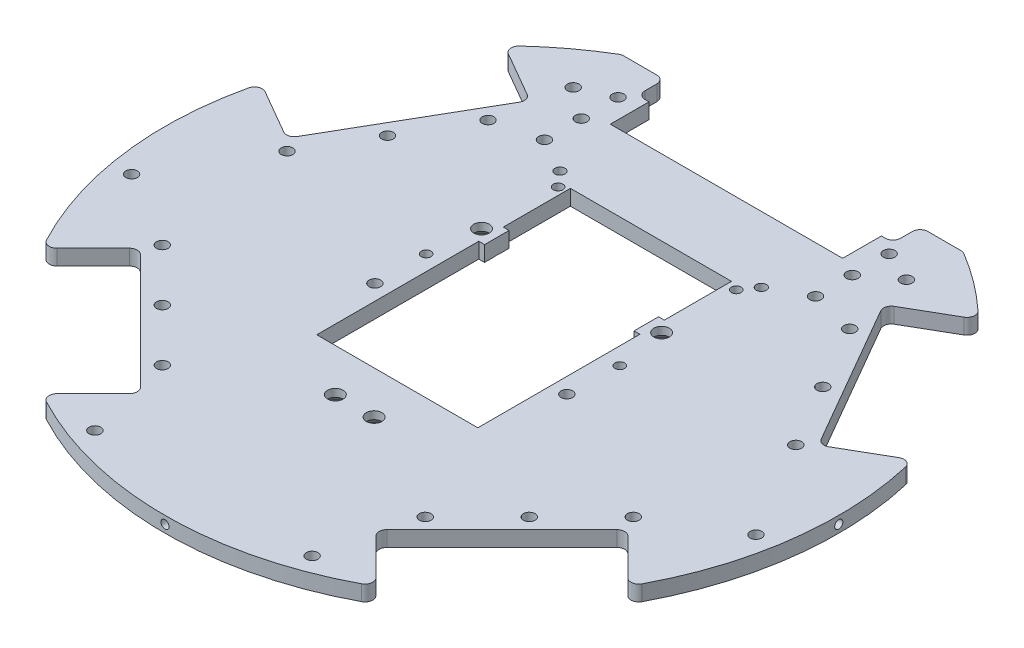
SolidWorks part; units mm, degrees
ref_plane "Front Plane" through (0, 0, 0) normal (0, 0, 1) x (1, 0, 0)
ref_plane "Top Plane" through (0, 0, 0) normal (0, 1, 0) x (1, 0, 0)
ref_plane "Right Plane" through (0, 0, 0) normal (1, 0, 0) x (0, 0, -1)
sketch "Sketch1" plane through (0, 0, 0) normal (0, 1, 0) x (1, 0, 0)
  line L0 (0, 75) -> (0, -70.0325) construction
  line L1 (0, 0) -> (57.1577, 33) construction
  line L2 (0, 0) -> (46.669, -46.669) construction
  line L3 (45.6577, 52.9186) -> (68.6577, 13.0814)
  line L4 (-44.0908, 75) -> (44.0908, 75) construction
  line L5 (62.9325, -30.4056) -> (30.4056, -62.9325)
  line L6 (45.6577, 52.9186) -> (61.1636, 61.8709)
  line L7 (68.6577, 13.0814) -> (84.1636, 22.0338)
  line L8 (30.4056, -62.9325) -> (43.0661, -75.593)
  line L9 (62.9325, -30.4056) -> (75.593, -43.0661)
  line L10 (-33, 69) -> (33, 69)
  line L11 (33, 69) -> (33, 75)
  line L12 (33, 75) -> (44.0908, 75)
  line L13 (0, 0) -> (-46.669, -46.669) construction
  line L14 (0, 0) -> (-57.1577, 33) construction
  line L15 (-33, 75) -> (-44.0908, 75)
  line L16 (-33, 69) -> (-33, 75)
  line L17 (-62.9325, -30.4056) -> (-75.593, -43.0661)
  line L18 (-30.4056, -62.9325) -> (-43.0661, -75.593)
  line L19 (-68.6577, 13.0814) -> (-84.1636, 22.0338)
  line L20 (-45.6577, 52.9186) -> (-61.1636, 61.8709)
  line L21 (-62.9325, -30.4056) -> (-30.4056, -62.9325)
  line L22 (-45.6577, 52.9186) -> (-68.6577, 13.0814)
  arc A0 (-43.0661, -75.593) -> (43.0661, -75.593) centre (0, 0) ccw
  arc A1 (61.1636, 61.8709) -> (44.0908, 75) centre (0, 0) ccw
  arc A2 (75.593, -43.0661) -> (84.1636, 22.0338) centre (0, 0) ccw
  arc A3 (-75.593, -43.0661) -> (-84.1636, 22.0338) centre (0, 0) cw
  arc A4 (-61.1636, 61.8709) -> (-44.0908, 75) centre (0, 0) cw
  point P27 (0, 69)
  dimension "D1" = 87
  dimension "D2" = 75
  dimension "D3" = 66
  dimension "D4" = 60
  dimension "D5" = 45
  dimension "D6" = 46
  dimension "D7" = 46
  dimension "D8" = 33
  dimension "D9" = 6
extrude "Boss-Extrude1" add sketch "Sketch1" along normal mid plane 4
fillet "Fillet1" radius 2 20 edges at (33, 0, -75) (-33, 0, -75) (44.0908, 0, -75) (68.6577, 0, -13.0814) (84.1636, 0, -22.0338) (45.6577, 0, -52.9186) (61.1636, 0, -61.8709) (62.9325, 0, 30.4056) (43.0661, 0, 75.593) (30.4056, 0, 62.9325) (75.593, 0, 43.0661) (-43.0661, 0, 75.593) (-30.4056, 0, 62.9325) (-75.593, 0, 43.0661) (-62.9325, 0, 30.4056) (-68.6577, 0, -13.0814) (-84.1636, 0, -22.0338) (-45.6577, 0, -52.9186) (-44.0908, 0, -75) (-61.1636, 0, -61.8709)
sketch "Sketch2" plane through (0, -2, 0) normal (0, -1, 0) x (-1, 0, 0)
  line L0 (46.6936, 43.1244) -> (65.6936, 10.2154) construction
  line L1 (60.8112, -26.8701) -> (33.9411, -53.7401) construction
  line L2 (46.6577, 51.1865) -> (67.6577, 14.8135) construction
  line L3 (61.5183, -31.8198) -> (31.8198, -61.5183) construction
  line L4 (70.3897, 14.0814) -> (81.8562, 20.7016) construction
  line L5 (73.7091, -41.1822) -> (64.3467, -31.8198) construction
  line L6 (35, 65) -> (35, 46) construction
  line L7 (26, 61) -> (26, 41) construction
  line L8 (35, 75) -> (43.5431, 75) construction
  line L9 (-33, 69) -> (33, 69) construction
  line L10 (-33, 69) -> (33, 69) construction
  line L11 (0, 69) -> (0, -87) construction
  line L12 (-26, 61) -> (-26, 41) construction
  line L13 (-35, 65) -> (-35, 46) construction
  line L14 (-60.8112, -26.8701) -> (-33.9411, -53.7401) construction
  line L15 (-46.6936, 43.1244) -> (-65.6936, 10.2154) construction
  arc A0 (-40.7037, -76.8909) -> (40.7037, -76.8909) centre (0, 0) ccw construction
  point P0 (46.6936, 43.1244)
  point P1 (56.1936, 26.6699)
  point P2 (65.6936, 10.2154)
  point P3 (60.8112, -26.8701)
  point P4 (47.3762, -40.3051)
  point P5 (33.9411, -53.7401)
  point P18 (35, 65)
  point P19 (35, 55.5)
  point P20 (35, 46)
  point P21 (26, 61)
  point P22 (26, 41)
  point P29 (0, 69)
  point P34 (0, 69)
  point P48 (-35, 55.5)
  point P49 (-47.3762, -40.3051)
  point P50 (-56.1936, 26.6699)
  dimension "D1" = 38
  dimension "D2" = 38
  dimension "D3" = 4
  dimension "D4" = 4
  dimension "D5" = 18
  dimension "D6" = 18
  dimension "D7" = 19
  dimension "D8" = 35
  dimension "10" = 10
  dimension "D9" = 20
  dimension "D10" = 8
  dimension "D11" = 26
hole_wizard "CSK for M3 SFHCS1" positions "3DSketch1" profile "Sketch3" countersink size "M3" standard "ANSI Metric"
sketch3d "3DSketch1"
  point P0 (46.6936, -2, -43.1244)
  point P3 (56.1936, -2, -26.6699)
  point P6 (65.6936, -2, -10.2154)
  point P9 (60.8112, -2, 26.8701)
  point P12 (47.3762, -2, 40.3051)
  point P15 (33.9411, -2, 53.7401)
  point P18 (-33.9411, -2, 53.7401)
  point P21 (-47.3762, -2, 40.3051)
  point P24 (-60.8112, -2, 26.8701)
  point P27 (-46.6936, -2, -43.1244)
  point P30 (-56.1936, -2, -26.6699)
  point P33 (-65.6936, -2, -10.2154)
  point P36 (-35, -2, -65)
  point P39 (-35, -2, -55.5)
  point P42 (-35, -2, -46)
  point P45 (35, -2, -46)
  point P48 (35, -2, -55.5)
  point P51 (35, -2, -65)
sketch "Sketch3" plane through (46.6936, -2, -43.1244) normal (1, 0, 0) x (0, 0, -1)
  line L0 (0, 0) -> (0, 10.4013)
  line L1 (0, 10.4013) -> (1.5, 9.5)
  line L2 (1.5, 9.5) -> (1.5, 1.3)
  line L3 (1.5, 1.3) -> (2.8, 0)
  line L5 (2.8, 0) -> (0, 0)
  line L6 (-1.5, 1.3) -> (-2.8, 0) construction
  line L10 (0, 10.4013) -> (-1.5, 9.5) construction
  line L11 (0, -6.35) -> (0, 107.95) construction
  dimension "Hole Dia." = 3
  dimension "Hole Depth" = 9.5
  dimension "Near C'Sink Dia." = 5.6
  dimension "Near C'Sink Angle" = 90
  dimension "Drill Angle" = 118
sketch "Sketch4" plane through (0, -2, 0) normal (0, -1, 0) x (1, 0, 0)
  line L0 (0, 0) -> (-43.0182, -61.4364) construction
  line L1 (0, 0) -> (-28.0457, 77.0548) construction
  line L2 (0, -69) -> (0, 87) construction
  line L3 (0, 0) -> (-80.6164, 15) construction
  line L4 (0, -69) -> (0, 87) construction
  line L5 (0, 0) -> (80.6164, 15) construction
  line L6 (0, 0) -> (28.0457, 77.0548) construction
  line L7 (0, 0) -> (43.0182, -61.4364) construction
  dimension "D1" = 75
  dimension "D2" = 35
  dimension "D3" = 82
  dimension "D4" = 20
  dimension "D5" = 82
  dimension "D6" = 15
hole_wizard "CSK for M3 SFHCS2" positions "3DSketch2" profile "Sketch5" countersink size "M3" standard "ANSI Metric"
sketch3d "3DSketch2"
  point P0 (43.0182, -2, -61.4364)
  point P3 (80.6164, -2, 15)
  point P6 (28.0457, -2, 77.0548)
  point P9 (-28.0457, -2, 77.0548)
  point P12 (-80.6164, -2, 15)
  point P15 (-43.0182, -2, -61.4364)
sketch "Sketch5" plane through (43.0182, -2, -61.4364) normal (1, 0, 0) x (0, 0, -1)
  line L0 (0, 0) -> (0, 10.4013)
  line L1 (0, 10.4013) -> (1.5, 9.5)
  line L2 (1.5, 9.5) -> (1.5, 1.3)
  line L3 (1.5, 1.3) -> (2.8, 0)
  line L5 (2.8, 0) -> (0, 0)
  line L6 (-1.5, 1.3) -> (-2.8, 0) construction
  line L10 (0, 10.4013) -> (-1.5, 9.5) construction
  line L11 (0, -6.35) -> (0, 107.95) construction
  dimension "Hole Dia." = 3
  dimension "Hole Depth" = 9.5
  dimension "Near C'Sink Dia." = 5.6
  dimension "Near C'Sink Angle" = 90
  dimension "Drill Angle" = 118
hole_wizard "CSK for M3 SFHCS3" positions "3DSketch3" profile "Sketch6" countersink size "M3" standard "ANSI Metric"
sketch3d "3DSketch3"
  point P0 (26, -2, -41)
  point P3 (26, -2, -61)
  point P6 (-26, -2, -41)
  point P9 (-26, -2, -61)
sketch "Sketch6" plane through (26, -2, -41) normal (1, 0, 0) x (0, 0, -1)
  line L0 (0, 0) -> (0, 10.2811)
  line L1 (0, 10.2811) -> (1.3, 9.5)
  line L2 (1.3, 9.5) -> (1.3, 1)
  line L3 (1.3, 1) -> (2.3, 0)
  line L5 (2.3, 0) -> (0, 0)
  line L6 (-1.3, 1) -> (-2.3, 0) construction
  line L10 (0, 10.2811) -> (-1.3, 9.5) construction
  line L11 (0, -6.35) -> (0, 107.95) construction
  dimension "Hole Dia." = 2.6
  dimension "Hole Depth" = 9.5
  dimension "Near C'Sink Dia." = 4.6
  dimension "Near C'Sink Angle" = 90
  dimension "Drill Angle" = 118
sketch "Sketch7" plane through (0, 0, 0) normal (0, 1, 0) x (1, 0, 0)
  arc A0 (-84.8058, 19.4159) -> (-76.8909, -40.7037) centre (0, 0) ccw construction
  arc A1 (76.8909, -40.7037) -> (84.8058, 19.4159) centre (0, 0) ccw construction
  arc A2 (-40.7037, -76.8909) -> (40.7037, -76.8909) centre (0, 0) ccw construction
  arc A3 (59.2176, 63.736) -> (44.5676, 74.7176) centre (0, 0) ccw construction
  arc A4 (-44.5676, 74.7176) -> (-59.2176, 63.736) centre (0, 0) ccw construction
  point P0 (-86.2557, -11.3558)
  point P1 (86.2557, -11.3558)
  point P5 (0, -87)
  point P9 (52.1823, 69.6133)
  point P13 (-52.1823, 69.6133)
ref_plane "Plane1" through (87, 0, 0) normal (1, 0, 0) x (0, 0, -1)
sketch "Sketch9" plane through (87, 0, 0) normal (1, 0, 0) x (0, 0, -1)
  circle A0 centre (0, 0) radius 1.05
  dimension "D1" = 2.1
ref_plane "Plane2" through (0, 0, 87) normal (0, 0, 1) x (1, 0, 0)
sketch "Sketch10" plane through (0, 0, 87) normal (0, 0, 1) x (1, 0, 0)
  circle A0 centre (0, 0) radius 1.05
  dimension "D1" = 2.1
ref_plane "Plane3" through (52.1823, 0, -69.6133) normal (0.5998, 0, -0.8002) x (-0.8002, 0, -0.5998)
sketch "Sketch11" plane through (52.1823, 0, -69.6133) normal (0.5998, 0, -0.8002) x (-0.8002, 0, -0.5998)
  circle A0 centre (0, 0) radius 1.05
  dimension "D1" = 2.1
sketch "Sketch12" plane through (0, 2, 0) normal (0, 1, 0) x (1, 0, 0)
  line L0 (-23.25, 18) -> (23.25, 18) construction
  line L1 (24.78, -8) -> (-24.78, -8) construction
  line L2 (-5, -38) -> (5, -38) construction
  line L3 (33, 69) -> (-33, 69) construction
  line L4 (-35, 75) -> (-43.5431, 75) construction
  point P0 (-23.25, 18)
  point P1 (23.25, 18)
  point P2 (-5, -38)
  point P3 (5, -38)
  point P4 (-24.78, -8)
  point P5 (24.78, -8)
  point P14 (0, 18)
  point P16 (0, -8)
  point P17 (0, -38)
  dimension "D1" = 51
  dimension "D2" = 83
  dimension "D3" = 56
  dimension "D4" = 49.56
  dimension "D5" = 10
  dimension "D6" = 46.5
sketch "Sketch14" plane through (0, -2, 0) normal (0, -1, 0) x (1, 0, 0)
  point P0 (23.25, -18)
  point P1 (-23.25, -18)
  point P3 (-24.78, 8)
  point P5 (24.78, 8)
  point P7 (5, 38)
  point P9 (-5, 38)
hole_wizard "CSK for M4 SFHCS3" positions "3DSketch7" profile "Sketch16" countersink size "M4" standard "ANSI Metric"
sketch3d "3DSketch7"
  point P0 (23.25, -2, -18)
  point P3 (-23.25, -2, -18)
  point P6 (-5, -2, 38)
  point P9 (5, -2, 38)
sketch "Sketch16" plane through (23.25, -2, -18) normal (1, 0, 0) x (0, 0, -1)
  line L0 (0, 0) -> (0, 10.7017)
  line L1 (0, 10.7017) -> (2, 9.5)
  line L2 (2, 9.5) -> (2, 2)
  line L3 (2, 2) -> (4, 0)
  line L5 (4, 0) -> (0, 0)
  line L6 (-2, 2) -> (-4, 0) construction
  line L10 (0, 10.7017) -> (-2, 9.5) construction
  line L11 (0, -6.35) -> (0, 107.95) construction
  dimension "Hole Dia." = 4
  dimension "Hole Depth" = 9.5
  dimension "Near C'Sink Dia." = 8
  dimension "Near C'Sink Angle" = 90
  dimension "Drill Angle" = 118
hole_wizard "CSK for M3 SFHCS4" positions "3DSketch8" profile "Sketch17" countersink size "M3" standard "ANSI Metric"
sketch3d "3DSketch8"
  point P0 (24.78, -2, 8)
  point P3 (-24.78, -2, 8)
sketch "Sketch17" plane through (24.78, -2, 8) normal (1, 0, 0) x (0, 0, -1)
  line L0 (0, 0) -> (0, 10.4013)
  line L1 (0, 10.4013) -> (1.5, 9.5)
  line L2 (1.5, 9.5) -> (1.5, 1.3)
  line L3 (1.5, 1.3) -> (2.8, 0)
  line L5 (2.8, 0) -> (0, 0)
  line L6 (-1.5, 1.3) -> (-2.8, 0) construction
  line L10 (0, 10.4013) -> (-1.5, 9.5) construction
  line L11 (0, -6.35) -> (0, 107.95) construction
  dimension "Hole Dia." = 3
  dimension "Hole Depth" = 9.5
  dimension "Near C'Sink Dia." = 5.6
  dimension "Near C'Sink Angle" = 90
  dimension "Drill Angle" = 118
extrude "Cut-Extrude1" cut sketch "Sketch9" against normal blind 8
extrude "Cut-Extrude2" cut sketch "Sketch10" against normal blind 8
extrude "Cut-Extrude3" cut sketch "Sketch11" against normal blind 8
mirror "Mirror1" about plane through (0, 0, 0) normal (1, 0, 0) of "Cut-Extrude3", "Cut-Extrude2", "Cut-Extrude1"
sketch "Sketch18" plane through (0, 2, 0) normal (0, 1, 0) x (1, 0, 0)
  line L0 (-44.8999, 78) -> (44.8999, 78) construction
  line L1 (-35, 75) -> (-43.5431, 75) construction
  circle A0 centre (0, 0) radius 90 construction
  dimension "D1" = 180
  dimension "D2" = 3
hole_wizard "M2.5x0.45 Tapped Hole1" positions "3DSketch9" profile "Sketch19" tap size "M2.5x0.45" standard "ANSI Metric"
sketch3d "3DSketch9"
  line L0 (-35, 2, -75) -> (-43.5431, 2, -75) construction
  line L1 (43.5431, 2, -75) -> (35, 2, -75) construction
  line L2 (-35, -2, -75) -> (-43.5431, -2, -75) construction
  point P0 (-39.2715, 0, -75)
  point P2 (39.4456, 0, -75)
  point P11 (-39.2715, -2, -75)
  dimension "D1" = 2
  dimension "D2" = 2
sketch "Sketch19" plane through (-39.2715, 0, -75) normal (1, 0, 0) x (0, 1, 0)
  line L0 (0, 0) -> (0, 6.9659)
  line L1 (0, 6.9659) -> (1.025, 6.35)
  line L2 (1.025, 6.35) -> (1.025, 0)
  line L5 (1.025, 0) -> (0, 0)
  line L10 (0, 6.9659) -> (-1.025, 6.35) construction
  line L11 (0, -6.35) -> (0, 107.95) construction
  dimension "Tap Drill Dia." = 2.05
  dimension "Tap Drill Depth" = 6.35
  dimension "Drill Angle" = 118
sketch "Sketch21" plane through (0, 2, 0) normal (0, 1, 0) x (1, 0, 0)
  line L17 (43.5431, 75) -> (35, 75)
  line L18 (33, 73) -> (33, 69)
  line L19 (33, 69) -> (-33, 69)
  line L20 (-33, 69) -> (-33, 73)
  line L21 (-35, 75) -> (-43.5431, 75)
  line L22 (-58.8562, 60.5388) -> (-47.3897, 53.9186)
  line L23 (-46.6577, 51.1865) -> (-67.6577, 14.8135)
  line L24 (-70.3897, 14.0814) -> (-81.8562, 20.7016)
  line L25 (-73.7091, -41.1822) -> (-64.3467, -31.8198)
  line L26 (-61.5183, -31.8198) -> (-31.8198, -61.5183)
  line L27 (-31.8198, -64.3467) -> (-41.1822, -73.7091)
  line L28 (41.1822, -73.7091) -> (31.8198, -64.3467)
  line L29 (31.8198, -61.5183) -> (61.5183, -31.8198)
  line L30 (64.3467, -31.8198) -> (73.7091, -41.1822)
  line L31 (81.8562, 20.7016) -> (70.3897, 14.0814)
  line L32 (67.6577, 14.8135) -> (46.6577, 51.1865)
  line L33 (47.3897, 53.9186) -> (58.8562, 60.5388)
  line L34 (43.5431, 75) -> (35, 75)
  line L35 (33, 73) -> (33, 69)
  line L36 (33, 69) -> (-33, 69)
  line L37 (-33, 69) -> (-33, 73)
  line L38 (-35, 75) -> (-43.5431, 75)
  line L39 (-58.8562, 60.5388) -> (-47.3897, 53.9186)
  line L40 (-46.6577, 51.1865) -> (-67.6577, 14.8135)
  line L41 (-70.3897, 14.0814) -> (-81.8562, 20.7016)
  line L42 (-73.7091, -41.1822) -> (-64.3467, -31.8198)
  line L43 (-61.5183, -31.8198) -> (-31.8198, -61.5183)
  line L44 (-31.8198, -64.3467) -> (-41.1822, -73.7091)
  line L45 (41.1822, -73.7091) -> (31.8198, -64.3467)
  line L46 (31.8198, -61.5183) -> (61.5183, -31.8198)
  line L47 (64.3467, -31.8198) -> (73.7091, -41.1822)
  line L48 (81.8562, 20.7016) -> (70.3897, 14.0814)
  line L49 (67.6577, 14.8135) -> (46.6577, 51.1865)
  line L50 (47.3897, 53.9186) -> (58.8562, 60.5388)
  circle A1 centre (25.24, 5.2127) radius 1.25
  circle A2 centre (25.24, 5.2127) radius 1.25
  circle A3 centre (-24.76, 5.2127) radius 1.25
  circle A4 centre (-24.76, 5.2127) radius 1.25
  circle A5 centre (-22.685, 37.2127) radius 1.25
  circle A6 centre (-22.685, 37.2127) radius 1.25
  circle A7 centre (23.315, 37.2127) radius 1.25
  circle A8 centre (23.315, 37.2127) radius 1.25
  arc A27 (35, 75) -> (33, 73) centre (35, 73) ccw
  arc A30 (-33, 73) -> (-35, 75) centre (-35, 73) ccw
  arc A31 (-43.5431, 75) -> (-44.5676, 74.7176) centre (-43.5431, 73) ccw
  arc A32 (-44.5676, 74.7176) -> (-59.2176, 63.736) centre (0, 0) ccw
  arc A33 (-59.2176, 63.736) -> (-58.8562, 60.5388) centre (-57.8562, 62.2708) ccw
  arc A34 (-46.6577, 51.1865) -> (-47.3897, 53.9186) centre (-48.3897, 52.1865) ccw
  arc A35 (-70.3897, 14.0814) -> (-67.6577, 14.8135) centre (-69.3897, 15.8135) ccw
  arc A36 (-81.8562, 20.7016) -> (-84.8058, 19.4159) centre (-82.8562, 18.9696) ccw
  arc A37 (-84.8058, 19.4159) -> (-76.8909, -40.7037) centre (0, 0) ccw
  arc A38 (-76.8909, -40.7037) -> (-73.7091, -41.1822) centre (-75.1233, -39.768) ccw
  arc A39 (-61.5183, -31.8198) -> (-64.3467, -31.8198) centre (-62.9325, -33.234) ccw
  arc A40 (-31.8198, -64.3467) -> (-31.8198, -61.5183) centre (-33.234, -62.9325) ccw
  arc A41 (-41.1822, -73.7091) -> (-40.7037, -76.8909) centre (-39.768, -75.1233) ccw
  arc A42 (-40.7037, -76.8909) -> (40.7037, -76.8909) centre (0, 0) ccw
  arc A43 (40.7037, -76.8909) -> (41.1822, -73.7091) centre (39.768, -75.1233) ccw
  arc A44 (31.8198, -61.5183) -> (31.8198, -64.3467) centre (33.234, -62.9325) ccw
  arc A45 (64.3467, -31.8198) -> (61.5183, -31.8198) centre (62.9325, -33.234) ccw
  arc A46 (73.7091, -41.1822) -> (76.8909, -40.7037) centre (75.1233, -39.768) ccw
  arc A47 (76.8909, -40.7037) -> (84.8058, 19.4159) centre (0, 0) ccw
  arc A48 (84.8058, 19.4159) -> (81.8562, 20.7016) centre (82.8562, 18.9696) ccw
  arc A49 (67.6577, 14.8135) -> (70.3897, 14.0814) centre (69.3897, 15.8135) ccw
  arc A50 (47.3897, 53.9186) -> (46.6577, 51.1865) centre (48.3897, 52.1865) ccw
  arc A51 (58.8562, 60.5388) -> (59.2176, 63.736) centre (57.8562, 62.2708) ccw
  arc A52 (59.2176, 63.736) -> (44.5676, 74.7176) centre (0, 0) ccw
  arc A53 (44.5676, 74.7176) -> (43.5431, 75) centre (43.5431, 73) ccw
  arc A54 (35, 75) -> (33, 73) centre (35, 73) ccw
  arc A57 (-33, 73) -> (-35, 75) centre (-35, 73) ccw
  arc A58 (-43.5431, 75) -> (-44.5676, 74.7176) centre (-43.5431, 73) ccw
  arc A59 (-44.5676, 74.7176) -> (-59.2176, 63.736) centre (0, 0) ccw
  arc A60 (-59.2176, 63.736) -> (-58.8562, 60.5388) centre (-57.8562, 62.2708) ccw
  arc A61 (-46.6577, 51.1865) -> (-47.3897, 53.9186) centre (-48.3897, 52.1865) ccw
  arc A62 (-70.3897, 14.0814) -> (-67.6577, 14.8135) centre (-69.3897, 15.8135) ccw
  arc A63 (-81.8562, 20.7016) -> (-84.8058, 19.4159) centre (-82.8562, 18.9696) ccw
  arc A64 (-84.8058, 19.4159) -> (-76.8909, -40.7037) centre (0, 0) ccw
  arc A65 (-76.8909, -40.7037) -> (-73.7091, -41.1822) centre (-75.1233, -39.768) ccw
  arc A66 (-61.5183, -31.8198) -> (-64.3467, -31.8198) centre (-62.9325, -33.234) ccw
  arc A67 (-31.8198, -64.3467) -> (-31.8198, -61.5183) centre (-33.234, -62.9325) ccw
  arc A68 (-41.1822, -73.7091) -> (-40.7037, -76.8909) centre (-39.768, -75.1233) ccw
  arc A69 (-40.7037, -76.8909) -> (40.7037, -76.8909) centre (0, 0) ccw
  arc A70 (40.7037, -76.8909) -> (41.1822, -73.7091) centre (39.768, -75.1233) ccw
  arc A71 (31.8198, -61.5183) -> (31.8198, -64.3467) centre (33.234, -62.9325) ccw
  arc A72 (64.3467, -31.8198) -> (61.5183, -31.8198) centre (62.9325, -33.234) ccw
  arc A73 (73.7091, -41.1822) -> (76.8909, -40.7037) centre (75.1233, -39.768) ccw
  arc A74 (76.8909, -40.7037) -> (84.8058, 19.4159) centre (0, 0) ccw
  arc A75 (84.8058, 19.4159) -> (81.8562, 20.7016) centre (82.8562, 18.9696) ccw
  arc A76 (67.6577, 14.8135) -> (70.3897, 14.0814) centre (69.3897, 15.8135) ccw
  arc A77 (47.3897, 53.9186) -> (46.6577, 51.1865) centre (48.3897, 52.1865) ccw
  arc A78 (58.8562, 60.5388) -> (59.2176, 63.736) centre (57.8562, 62.2708) ccw
  arc A79 (59.2176, 63.736) -> (44.5676, 74.7176) centre (0, 0) ccw
  arc A80 (44.5676, 74.7176) -> (43.5431, 75) centre (43.5431, 73) ccw
  dimension "D1" = 0
  dimension "D2" = 0
  dimension "D3" = 0
  dimension "D4" = 0
  dimension "D5" = 0
extrude "Cut-Extrude4" cut sketch "Sketch21" against normal up to next contours A2 | A8 | A4 | A6
sketch "Sketch23" plane through (0, 0, -69) normal (0, 0, -1) x (-1, 0, 0)
  line L1 (33, -2) -> (-33, -2)
  line L2 (33, -2) -> (33, 2)
  line L3 (33, 2) -> (-33, 2)
  line L4 (-33, -2) -> (-33, 2)
extrude "Cut-Extrude6" cut sketch "Sketch23" against normal blind 1
fillet "Fillet2" radius 2 2 edges at (33, 0, -68) (-33, 0, -68)
sketch "Sketch24" plane through (0, -2, 0) normal (0, -1, 0) x (1, 0, 0)
  line L0 (31, -68) -> (-31, -68) construction
  line L1 (-20.8, 27) -> (20.8, 27)
  line L2 (-20.8, 27) -> (-20.8, -14.8381)
  line L3 (-20.8, -38.5) -> (20.8, -38.5)
  line L4 (20.8, 27) -> (20.8, -14.8381)
  line L5 (-20.8, -14.8381) -> (-19.3, -14.8381)
  line L6 (-19.3, -14.8381) -> (-19.3, -21.1619)
  line L7 (-19.3, -21.1619) -> (-20.8, -21.1619)
  line L8 (-20.8, -21.1619) -> (-20.8, -38.5)
  line L9 (20.8, -14.8381) -> (19.3, -14.8381)
  line L10 (19.3, -14.8381) -> (19.3, -21.1619)
  line L11 (19.3, -21.1619) -> (20.8, -21.1619)
  line L12 (20.8, -21.1619) -> (20.8, -38.5)
  circle A0 centre (-23.25, -18) radius 4 construction
  circle A1 centre (23.25, -18) radius 4 construction
  point P6 (0, -68)
  point P7 (0, 27)
  dimension "D1" = 29.5
  dimension "D2" = 41.6
  dimension "D3" = 65.5
  dimension "D4" = 1.5
  dimension "D5" = 1.5
extrude "Cut-Extrude9" cut sketch "Sketch24" against normal blind 10 contours L2 L5 L6 L7 L8 L3 L12 L11 L10 L9 L4 L1
sketch "Sketch25" plane through (0, 0, -68) normal (0, 0, -1) x (-1, 0, 0)
  line L0 (31, 2) -> (-31, 2) construction
  line L1 (-30, 2) -> (30, 2)
  line L2 (-30, 2) -> (-30, -2)
  line L3 (-30, -2) -> (30, -2)
  line L4 (30, 2) -> (30, -2)
  line L5 (-31, -2) -> (31, -2) construction
  line L6 (-31, 2) -> (-31, -2) construction
  line L7 (31, -2) -> (31, 2) construction
  dimension "D1" = 1
  dimension "D2" = 1
extrude "Cut-Extrude10" cut sketch "Sketch25" against normal blind 10
